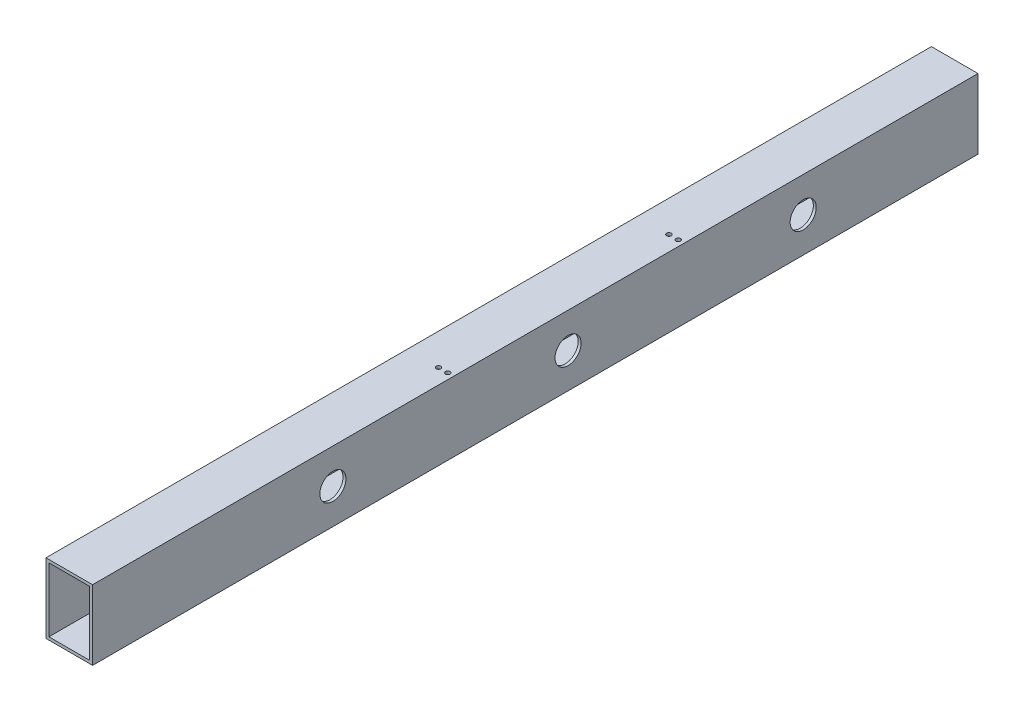
SolidWorks part; units mm, degrees
ref_plane "Front Plane" through (0, 0, 0) normal (0, 0, 1) x (1, 0, 0)
ref_plane "Top Plane" through (0, 0, 0) normal (0, 1, 0) x (1, 0, 0)
ref_plane "Right Plane" through (0, 0, 0) normal (1, 0, 0) x (0, 0, -1)
sketch "Sketch1" plane through (0, 0, 0) normal (0, 0, 1) x (1, 0, 0)
  line L0 (0, 38.1) -> (0, 34.925) construction
  line L1 (-25.4, 38.1) -> (25.4, 38.1)
  line L2 (-25.4, 38.1) -> (-25.4, -38.1)
  line L3 (-25.4, -38.1) -> (25.4, -38.1)
  line L4 (25.4, 38.1) -> (25.4, -38.1)
  line L5 (-25.4, 38.1) -> (25.4, -38.1) construction
  line L6 (-25.4, -38.1) -> (25.4, 38.1) construction
  line L7 (-22.225, 34.925) -> (22.225, 34.925)
  line L8 (-22.225, 34.925) -> (-22.225, -34.925)
  line L9 (-22.225, -34.925) -> (22.225, -34.925)
  line L10 (22.225, 34.925) -> (22.225, -34.925)
  line L11 (22.225, 0) -> (25.4, 0) construction
  line L12 (-22.225, 0) -> (-25.4, 0) construction
  line L13 (0, -34.925) -> (0, -38.1) construction
  point P0 (0, 0)
  dimension "D1" = 76.2
  dimension "D2" = 50.8
  dimension "D3" = 3.175
extrude "Boss-Extrude1" add sketch "Sketch1" along normal blind 965.2
sketch "Sketch2" plane through (0, 38.1, 0) normal (0, 1, 0) x (1, 0, 0)
  line L0 (-26.9875, -190.549) -> (26.9875, -190.549) construction
  line L1 (-25.4, 0) -> (25.4, 0)
  line L2 (-25.4, 0) -> (-25.4, -965.2)
  line L3 (-25.4, -965.2) -> (25.4, -965.2)
  line L4 (25.4, 0) -> (25.4, -965.2)
  line L5 (-26.4963, -703.2466) -> (26.4963, -703.2466) construction
  line L6 (0, -703.2466) -> (0, -190.549) construction
  line L7 (0, 0) -> (0, -190.549) construction
  line L8 (-74.6125, -402.6047) -> (-73.6301, -528.6965) construction
  line L9 (-74.1213, -465.6506) -> (-23.8125, -465.6506) construction
  line L10 (-23.8125, -465.6506) -> (26.9875, -465.6506) construction
  line L11 (21.8023, -571.6147) -> (25.4, -571.6147) construction
  line L12 (21.8023, -569.9256) -> (21.8023, -573.3038) construction
  line L13 (21.8023, -571.6147) -> (0, -571.6147) construction
  line L14 (0, -322.121) -> (25.4, -322.121) construction
  dimension "D1" = 190.549
  dimension "D2" = 512.6976
  dimension "D3" = 126.0917
  dimension "D4" = 50.3088
  dimension "D5" = 50.8
  dimension "D6" = 53.975
  dimension "D7" = 52.9926
  dimension "D8" = 275.1016
  dimension "D9" = 131.6319
  dimension "D10" = 131.572
ref_plane "Plane1" through (25.4, 0, 0) normal (1, 0, 0) x (0, 0, -1)
sketch "Sketch4" plane through (25.4, 0, 0) normal (1, 0, 0) x (0, 0, -1)
  line L0 (-703.2466, 38.1) -> (-703.2466, 0) construction
  line L1 (-703.2466, 38.1) -> (-190.549, 38.1) construction
  line L2 (-190.549, 38.1) -> (-190.549, 0) construction
  line L3 (0, 38.1) -> (-190.549, 38.1) construction
  line L4 (-190.549, 0) -> (0, 0) construction
  line L5 (0, -38.1) -> (0, 38.1) construction
  line L6 (-190.549, 0) -> (-703.2466, 0) construction
  line L7 (-446.8978, 0) -> (-446.8978, 38.1) construction
  line L8 (-402.6047, 38.1) -> (-528.6965, 38.1) construction
  circle A0 centre (-703.2466, 0) radius 14.224
  circle A1 centre (-190.549, 0) radius 14.224
  circle A2 centre (-446.8978, 0) radius 14.224
  dimension "D1" = 28.448
  dimension "D2" = 512.6976
  dimension "D3" = 190.549
extrude "Cut-Extrude1" cut sketch "Sketch4" against normal up to surface (50.8 mm away) up to face at (-25.4, 0, 482.6)
ref_plane "Plane2" through (0, 38.1, 0) normal (0, 1, 0) x (1, 0, 0)
sketch "Sketch5" plane through (0, 38.1, 0) normal (0, 1, 0) x (1, 0, 0)
  line L0 (5.08, -571.6147) -> (25.4, -571.6147) construction
  line L1 (21.8023, -571.6147) -> (0, -571.6147) construction
  line L2 (25.4, -575.4247) -> (5.08, -575.4247) construction
  line L3 (15.24, -320.4738) -> (15.24, -569.9675) construction
  line L4 (0, -322.121) -> (25.4, -322.121) construction
  line L5 (22.86, -324.2838) -> (22.86, -316.6638) construction
  line L6 (25.4, -571.6147) -> (25.4, -567.8047) construction
  line L7 (25.4, 0) -> (25.4, -965.2) construction
  line L8 (25.4, -567.8047) -> (5.08, -567.8047) construction
  line L9 (5.08, -567.8047) -> (5.08, -575.4247) construction
  line L10 (22.86, -567.8047) -> (22.86, -575.4247) construction
  line L11 (15.24, -571.6147) -> (15.24, -322.121) construction
  line L12 (15.24, -446.0443) -> (0, -446.0443) construction
  line L13 (0, -703.2466) -> (0, -190.549) construction
  line L14 (15.24, -446.0443) -> (25.4, -446.0443) construction
  line L15 (5.08, -324.2838) -> (5.08, -316.6638) construction
  line L16 (25.4, -324.2838) -> (5.08, -324.2838) construction
  line L17 (25.4, -316.6638) -> (5.08, -316.6638) construction
  line L18 (5.08, -320.4738) -> (25.4, -320.4738) construction
  circle A4 centre (8.89, -571.6147) radius 2.5006
  circle A5 centre (19.05, -571.6147) radius 2.5006
  circle A6 centre (19.05, -320.4738) radius 2.5006
  circle A7 centre (8.89, -320.4738) radius 2.5006
  dimension "D1" = 5.0013
  dimension "D2" = 2.54
  dimension "D5" = 3.81
  dimension "D6" = 3.81
  dimension "D7" = 20.32
  dimension "D8" = 3.81
extrude "Cut-Extrude2" cut sketch "Sketch5" against normal up to surface (3.175 mm away) up to face at (0, 34.925, 482.6)
